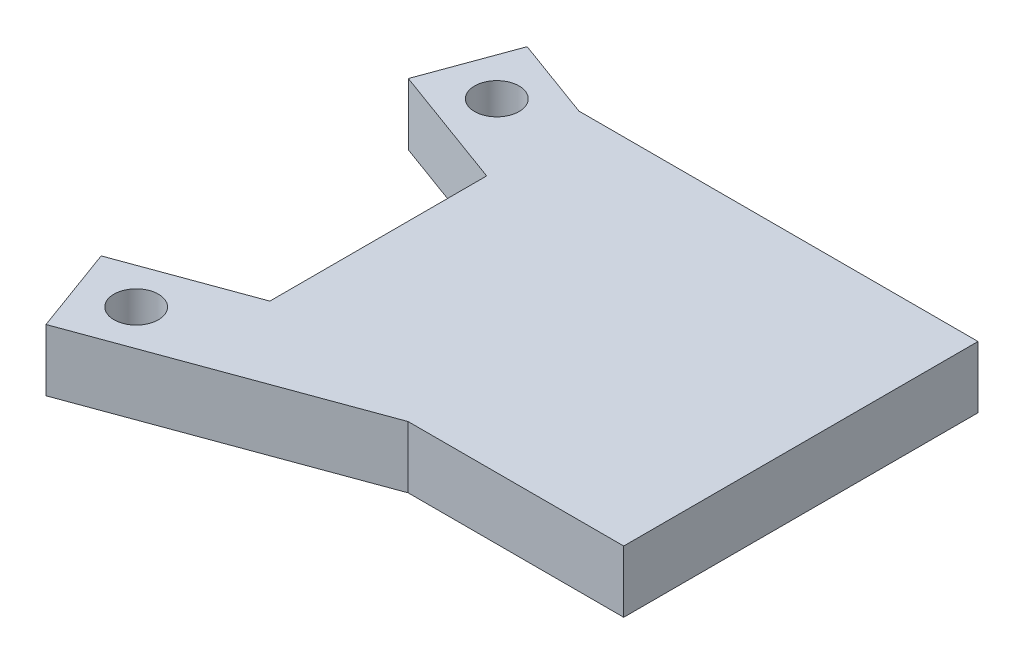
SolidWorks part; units mm, degrees
ref_plane "Front Plane" through (0, 0, 0) normal (0, 0, 1) x (1, 0, 0)
ref_plane "Top Plane" through (0, 0, 0) normal (0, 1, 0) x (1, 0, 0)
ref_plane "Right Plane" through (0, 0, 0) normal (1, 0, 0) x (0, 0, -1)
sketch "Sketch1" plane through (0, 0, 0) normal (0, 1, 0) x (1, 0, 0)
  line L0 (21.2293, -21.8246) -> (29.626, -24.8972)
  line L1 (29.626, -24.8972) -> (70.6611, -24.8972)
  line L5 (70.6611, -24.8972) -> (70.6611, -61.3274)
  line L7 (30.6561, -57.7105) -> (30.6561, -35.4168)
  line L8 (30.6561, -35.4168) -> (17.9561, -30.7695)
  line L9 (17.9561, -30.7695) -> (21.2293, -21.8246)
  line L12 (55.1375, -61.3274) -> (69.8674, -61.3274) construction
  line L13 (30.6561, -57.7105) -> (17.9561, -62.3578)
  line L14 (-48.9224, -86.8307) -> (30.1351, -57.9011) construction
  line L15 (17.9561, -62.3578) -> (21.2293, -71.3027)
  line L16 (50.6586, -60.5337) -> (-49.8568, -97.3153) construction
  line L17 (21.2293, -71.3027) -> (48.4895, -61.3274)
  line L18 (48.4895, -61.3274) -> (70.6611, -61.3274)
  line L21 (70.6611, -35.9716) -> (70.6611, -57.1557) construction
  line L25 (30.6561, -57.1557) -> (30.6561, -35.9716) construction
  line L26 (30.1351, -35.2262) -> (-48.9224, -6.2966) construction
  line L29 (-49.8568, 4.188) -> (29.5896, -24.8839) construction
  point P2 (0, 0)
  point P3 (69.21, -24.8972)
  point P6 (70.6611, -38.6864)
  dimension "D1" = 12.7
  dimension "D3" = 12.7
extrude "Boss-Extrude1" add sketch "Sketch1" along normal blind 6.35
sketch "Sketch2" plane through (0, 6.35, 0) normal (0, 1, 0) x (1, 0, 0)
  line L0 (30.6561, -35.4168) -> (30.6561, -57.7105) construction
  line L2 (24.3061, -65.1055) -> (25.9427, -69.578) construction
  line L3 (21.2293, -71.3027) -> (48.4895, -61.3274) construction
  line L4 (24.3061, -65.1055) -> (22.6695, -60.633) construction
  line L5 (30.6561, -57.7105) -> (17.9561, -62.3578) construction
  line L6 (24.3061, -28.0218) -> (22.6695, -32.4943) construction
  line L7 (17.9561, -30.7695) -> (30.6561, -35.4168) construction
  line L8 (24.3061, -28.0218) -> (25.9427, -23.5494) construction
  line L9 (29.626, -24.8972) -> (21.2293, -21.8246) construction
  circle A10 centre (24.3061, -65.1055) radius 2.286
  circle A11 centre (24.3061, -28.0218) radius 2.286
  dimension "D1" = 6.35
  dimension "D4" = 4.572
  dimension "D2" = 6.35
extrude "Cut-Extrude1" cut sketch "Sketch2" against normal through all
